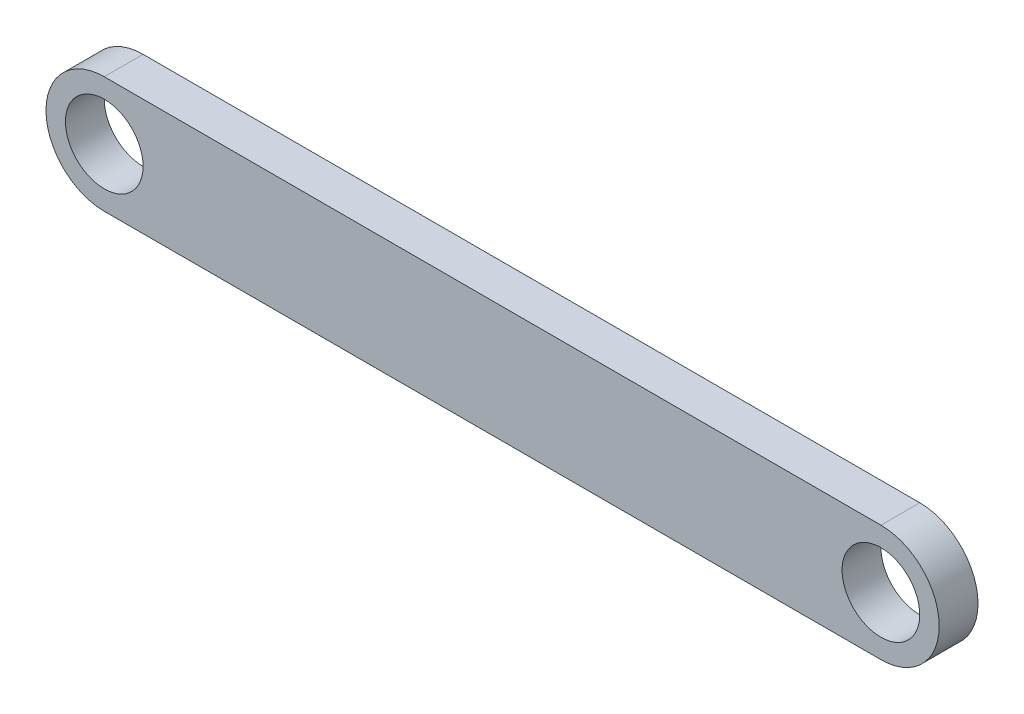
SolidWorks part; units mm, degrees
ref_plane "Front Plane" through (0, 0, 0) normal (0, 0, 1) x (1, 0, 0)
ref_plane "Top Plane" through (0, 0, 0) normal (0, 1, 0) x (1, 0, 0)
ref_plane "Right Plane" through (0, 0, 0) normal (1, 0, 0) x (0, 0, -1)
sketch "Sketch1" plane through (0, 0, 0) normal (0, 0, 1) x (1, 0, 0)
  line L0 (0, 0) -> (-200, 0) construction
  line L1 (0, -15) -> (-200, -15)
  line L2 (0, 15) -> (-200, 15)
  arc A0 (0, -15) -> (0, 15) centre (0, 0) ccw
  arc A1 (-200, 15) -> (-200, -15) centre (-200, 0) ccw
  circle A2 centre (-200, 0) radius 10
  circle A3 centre (0, 0) radius 10
  point P3 (-100, 0)
  dimension "D3" = 20
  dimension "D1" = 30
  dimension "D2" = 200
extrude "Boss-Extrude1" add sketch "Sketch1" along normal mid plane 10
